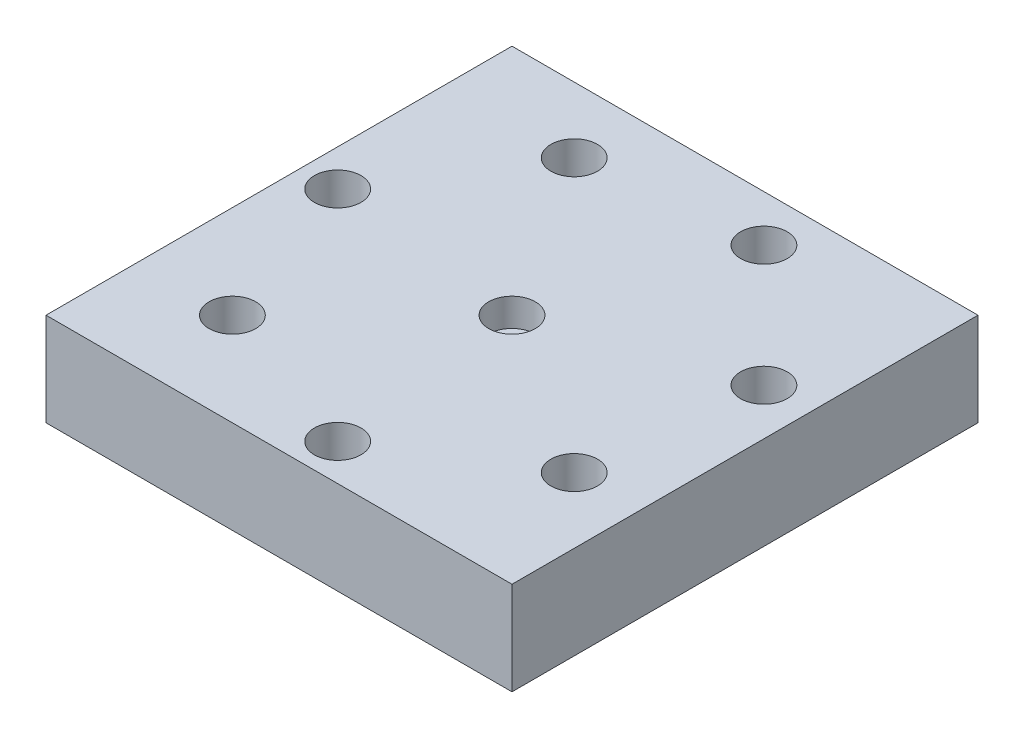
SolidWorks part; units mm, degrees
ref_plane "Front Plane" through (0, 0, 0) normal (0, 0, 1) x (1, 0, 0)
ref_plane "Top Plane" through (0, 0, 0) normal (0, 1, 0) x (1, 0, 0)
ref_plane "Right Plane" through (0, 0, 0) normal (1, 0, 0) x (0, 0, -1)
sketch "Sketch1" plane through (0, 0, 0) normal (0, 1, 0) x (1, 0, 0)
  line L1 (-635, -635) -> (635, -635)
  line L2 (-635, -635) -> (-635, 635)
  line L3 (-635, 635) -> (635, 635)
  line L4 (635, -635) -> (635, 635)
  line L5 (-635, -635) -> (635, 635) construction
  line L6 (-635, 635) -> (635, -635) construction
  circle A0 centre (-381, -381) radius 63.5
  circle A1 centre (-535.4274, 60.3282) radius 63.5
  circle A2 centre (-286.6671, 456.228) radius 63.5
  circle A3 centre (177.9594, 508.5788) radius 63.5
  circle A4 centre (508.5788, 177.9594) radius 63.5
  circle A5 centre (456.228, -286.6671) radius 63.5
  circle A6 centre (60.3282, -535.4274) radius 63.5
  point P0 (0, 0)
  point P22 (0, 0)
  dimension "D3" = 127
  dimension "D1" = 1270
  dimension "D2" = 1270
  dimension "D4" = 254
  dimension "D5" = 254
  dimension "D7" = 99.5726
  dimension "D8" = 695.3282
  dimension "D6" = 7
extrude "Boss-Extrude1" add sketch "Sketch1" along normal blind 254
hole_wizard "CBORE for #00 Binding Head Machine Screw1" positions "Sketch2" profile "Sketch3" counterbore size "#00" standard "ANSI Inch" end condition through all
sketch "Sketch2" plane through (0, 254, 0) normal (0, 1, 0) x (1, 0, 0)
  point P0 (0, 0)
sketch "Sketch3" plane through (0, 254, 0) normal (1, 0, 0) x (0, 0, 1)
  line L0 (0, 0) -> (0, 254)
  line L1 (0, 254) -> (38.1, 254)
  line L3 (38.1, 254) -> (38.1, 76.2)
  line L4 (38.1, 76.2) -> (63.5, 76.2)
  line L5 (63.5, 76.2) -> (63.5, 0)
  line L7 (63.5, 0) -> (0, 0)
  line L11 (0, -6.35) -> (0, 107.95) construction
  dimension "Thru Hole Dia." = 76.2
  dimension "Thru Hole Depth" = 254
  dimension "C'Bore Dia." = 127
  dimension "C'Bore Depth" = 76.2
